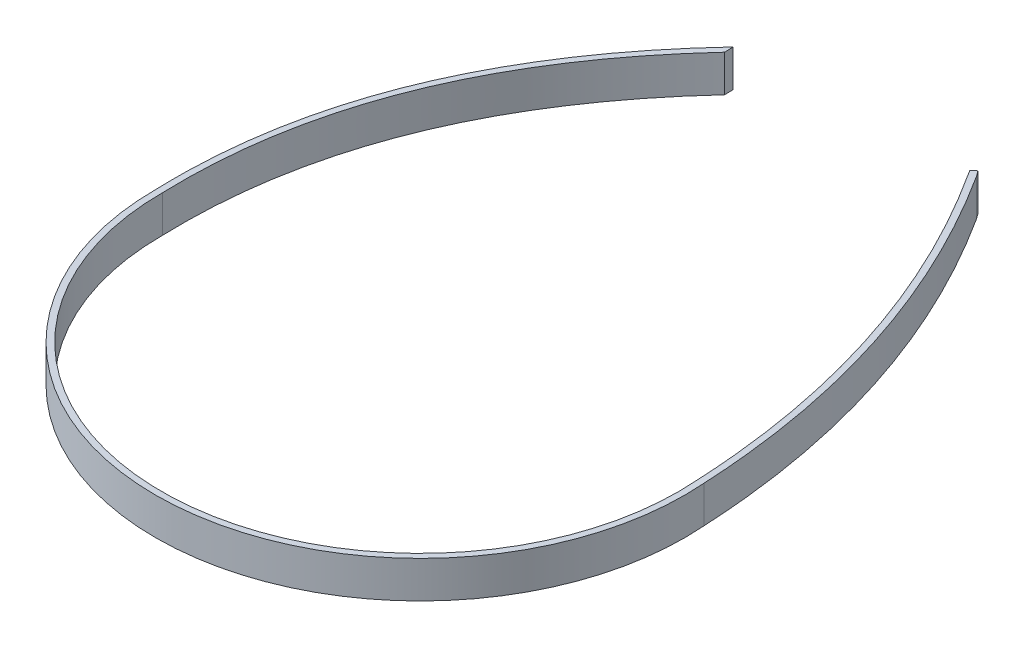
SolidWorks part; units mm, degrees
ref_plane "前视基准面" through (0, 0, 0) normal (0, 0, 1) x (1, 0, 0)
ref_plane "上视基准面" through (0, 0, 0) normal (0, 1, 0) x (1, 0, 0)
ref_plane "右视基准面" through (0, 0, 0) normal (1, 0, 0) x (0, 0, -1)
sketch "草图1" plane through (0, 0, 0) normal (0, 1, 0) x (1, 0, 0)
  line L0 (20.94, 1.5885) -> (20.9399, 1.5874)
  line L1 (-8.0725, 33.5) -> (-8.0513, 32.7872)
  line L15 (10.9275, 34.2658) -> (10.5882, 34.7343)
  line L21 (10.5882, 34.7343) -> (10.2368, 34.4171)
  line L31 (11.7695, 34.8052) -> (10.9275, 34.2658) construction
  line L32 (11.4999, 35.2262) -> (10.2368, 34.4171) construction
  arc A0 (-20.9999, 0.065) -> (20.9399, 1.5874) centre (0, 0) ccw
  arc A1 (-21.5, 0) -> (21.4394, 1.613) centre (0, 0) ccw
  spline S0 degree 2 poles (-8.0725, 33.5) (-22.1367, 18.5273) (-21.5, 0) knots 0 0 0 0.391212 0.391212 0.391212
  spline S1 degree 3 poles (-8.0513, 32.7872) (-8.6103, 32.1824) (-9.7144, 30.9392) (-11.752, 28.4415) (-14.0289, 25.2443) (-16.3117, 21.3079) (-18.1504, 17.2662) (-19.5451, 13.1209) (-20.4968, 8.8651) (-21.0045, 4.5309) (-21.049, 1.539) (-20.9999, 0.065) knots 0.004872 0.004872 0.004872 0.004872 0.02896 0.05311 0.10141 0.14971 0.198011 0.246311 0.294611 0.342912 0.390695 0.390695 0.390695 0.390695
  spline S2 degree 2 poles (10.9275, 34.2658) (20.5758, 19.2031) (21.4394, 1.613) knots 0 0 0 0.204405 0.204405 0.204405
  spline S6 degree 1 poles (10.2368, 34.4171) (20.94, 1.5885) knots 0 0 1 1 construction
  spline S7 degree 3 poles (10.2368, 34.4171) (11.0413, 33.1612) (12.6103, 30.6001) (15.3171, 25.4029) (18.0185, 18.698) (19.7793, 11.7245) (20.6291, 5.9929) (20.8681, 3.0536) (20.94, 1.5885) knots -0.002857 -0.002857 -0.002857 -0.002857 0.023051 0.048959 0.100774 0.15259 0.178497 0.204405 0.204405 0.204405 0.204405
  point P11 (10.9275, 36.5)
  point P16 (10.9275, 16.5)
  point P32 (-7.3437, 32.8154)
extrude "拉伸1" add sketch "草图1" along normal mid plane 3 contours A1 S2 L15 L21 S7 L0 A0 S1 L1 S0
